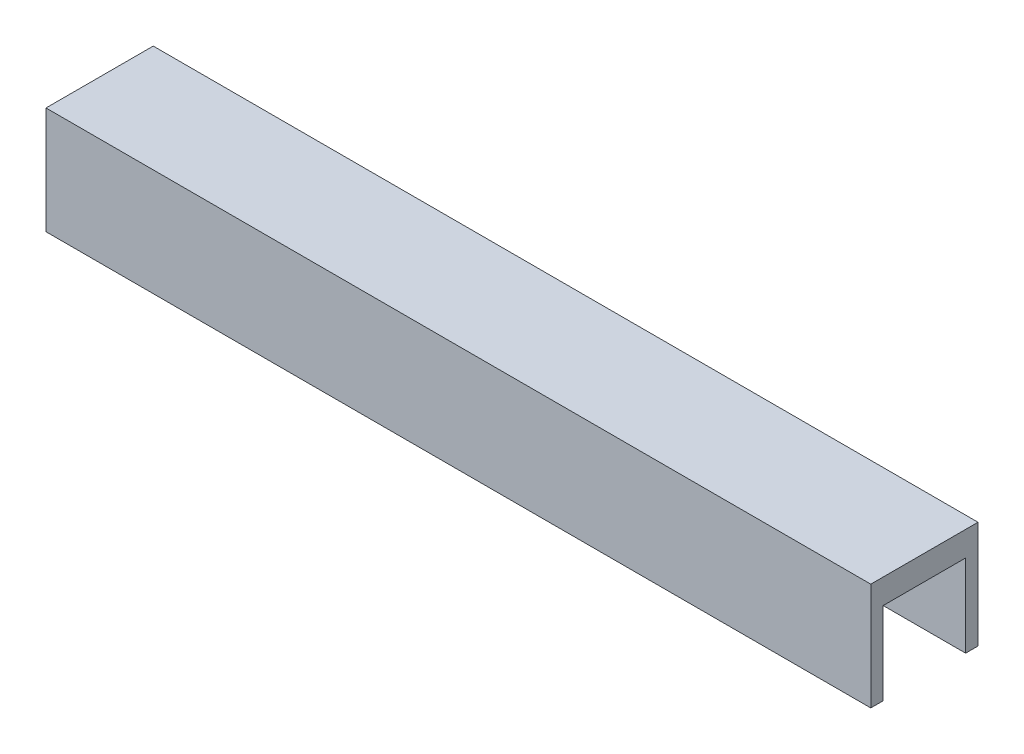
SolidWorks part; units mm, degrees
ref_plane "Front Plane" through (0, 0, 0) normal (0, 0, 1) x (1, 0, 0)
ref_plane "Top Plane" through (0, 0, 0) normal (0, 1, 0) x (1, 0, 0)
ref_plane "Right Plane" through (0, 0, 0) normal (1, 0, 0) x (0, 0, -1)
sketch "Sketch1" plane through (0, 0, 0) normal (0, 1, 0) x (1, 0, 0)
  line L1 (-50, -6.5) -> (50, -6.5)
  line L2 (-50, -6.5) -> (-50, 6.5)
  line L3 (-50, 6.5) -> (50, 6.5)
  line L4 (50, -6.5) -> (50, 6.5)
  point P0 (0, 0)
  dimension "D1" = 100
  dimension "D2" = 13
extrude "Boss-Extrude1" add sketch "Sketch1" along normal blind 13
ref_plane "Plane1" through (0, 10, 0) normal (0, 1, 0) x (1, 0, 0)
sketch "Sketch2" plane through (0, 10, 0) normal (0, 1, 0) x (1, 0, 0)
  line L0 (50, -6.5) -> (50, 6.5) construction
  line L1 (-50, -5) -> (50, -5)
  line L2 (-50, -5) -> (-50, 5)
  line L3 (-50, 5) -> (50, 5)
  line L4 (50, -5) -> (50, 5)
  line L5 (-50, -5) -> (50, 5) construction
  line L6 (-50, 5) -> (50, -5) construction
  point P0 (0, 0)
  dimension "D1" = 10
extrude "Cut-Extrude1" cut sketch "Sketch2" against normal blind 13
